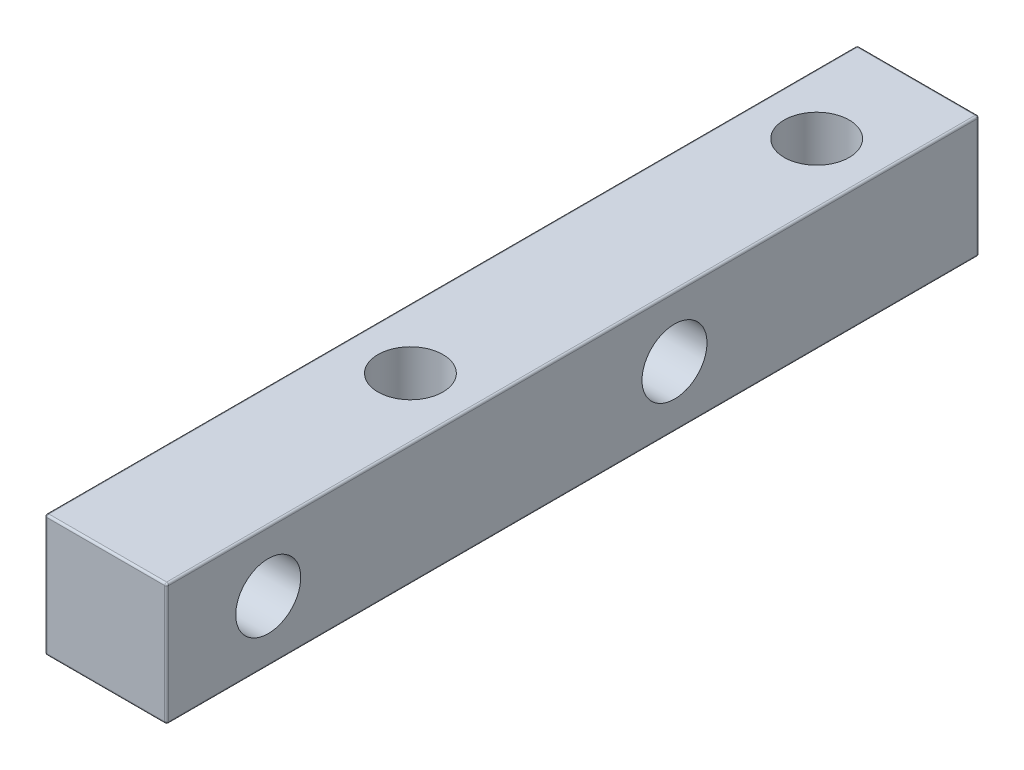
SolidWorks part; units mm, degrees
material "6061 合金"
ref_plane "Front Plane" through (0, 0, 0) normal (0, 0, 1) x (1, 0, 0)
ref_plane "Top Plane" through (0, 0, 0) normal (0, 1, 0) x (1, 0, 0)
ref_plane "Right Plane" through (0, 0, 0) normal (1, 0, 0) x (0, 0, -1)
other "Configuration Table"
sketch "草图1" plane through (0, 0, 0) normal (0, 0, 1) x (1, 0, 0)
  line L1 (-3, 3) -> (3, 3)
  line L2 (-3, 3) -> (-3, -3)
  line L3 (-3, -3) -> (3, -3)
  line L4 (3, 3) -> (3, -3)
  line L5 (-3, 3) -> (3, -3) construction
  line L6 (-3, -3) -> (3, 3) construction
  point P0 (0, 0)
  dimension "D1" = 6
  dimension "D2" = 6
extrude "凸台-拉伸1" add sketch "草图1" along normal blind 40
sketch "草图2" plane through (-3, 0, 0) normal (-1, 0, 0) x (0, 0, 1)
  line L0 (0, 0) -> (40, 0) construction
  line L1 (40, 3) -> (40, -3) construction
  line L2 (0, 3) -> (0, -3) construction
  circle A0 centre (15, 0) radius 1.6
  circle A1 centre (35, 0) radius 1.6
  dimension "D1" = 3.2
  dimension "D2" = 3.2
  dimension "D3" = 20
  dimension "D4" = 15
extrude "切除-拉伸1" cut sketch "草图2" against normal blind 40
sketch "草图3" plane through (0, 3, 0) normal (0, 1, 0) x (1, 0, 0)
  line L0 (0, 0) -> (0, -40) construction
  line L1 (3, -40) -> (-3, -40) construction
  line L2 (3, 0) -> (-3, 0) construction
  circle A0 centre (0, -5) radius 1.6
  circle A1 centre (0, -25) radius 1.6
  dimension "D1" = 3.2
  dimension "D2" = 20
  dimension "D3" = 5
extrude "切除-拉伸2" cut sketch "草图3" against normal blind 40
sketch "Sketch1" plane through (3, 0, 0) normal (1, 0, 0) x (0, 0, -1)
  line B0 (0, -3) -> (0, 3)
  line B1 (0, 3) -> (-40, 3)
  line B2 (-40, 3) -> (-40, -3)
  line B3 (-40, -3) -> (0, -3)
  circle B4 centre (-15, 0) radius 1.6
  circle B5 centre (-35, 0) radius 1.6
sketch_block_instance "Block1-1"
sketch_block "Block1"
fillet "圆角1" radius 0.1 12 edges at (3, 0, 0) (0, 3, 0) (-3, 0, 0) (0, -3, 0) (3, 0, 40) (0, 3, 40) (-3, 0, 40) (0, -3, 40) (3, -3, 20) (-3, -3, 20) (3, 3, 20) (-3, 3, 20)
